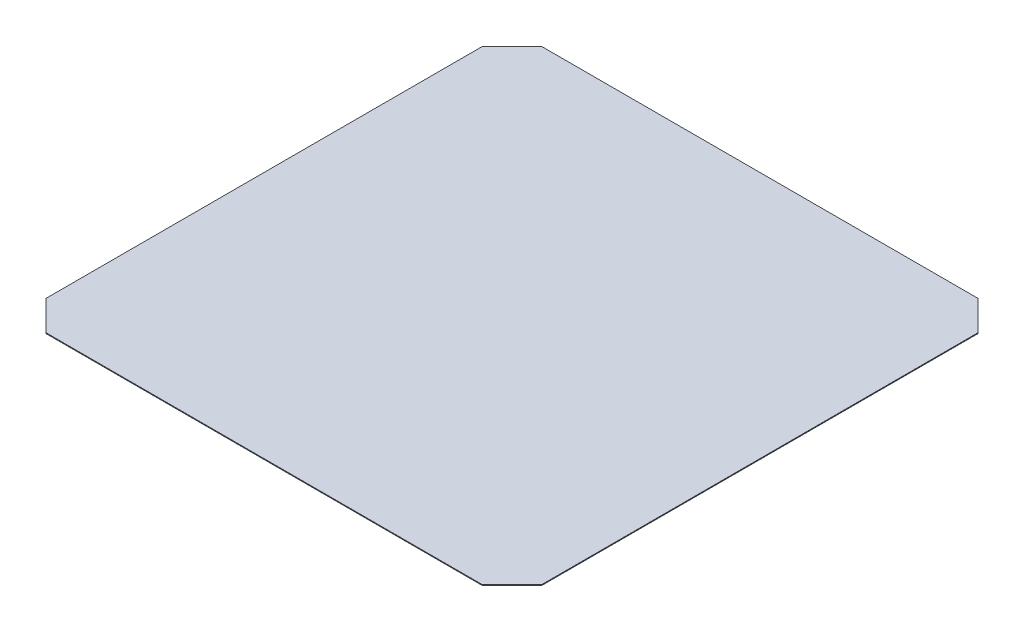
SolidWorks part; units mm, degrees
ref_plane "Alzado" through (0, 0, 0) normal (0, 0, 1) x (1, 0, 0)
ref_plane "Planta" through (0, 0, 0) normal (0, 1, 0) x (1, 0, 0)
ref_plane "Vista lateral" through (0, 0, 0) normal (1, 0, 0) x (0, 0, -1)
sketch "Croquis2" plane through (0, 0, 0) normal (0, 1, 0) x (1, 0, 0)
  line L0 (-62.5, 0) -> (62.5, 0) construction
  line L1 (0, -62.5) -> (0, 62.5) construction
  line L2 (-62.5, 0) -> (-62.5, 55)
  line L3 (-62.5, 55) -> (-55, 62.5)
  line L4 (-55, 62.5) -> (55, 62.5)
  line L5 (55, 62.5) -> (62.5, 55)
  line L6 (62.5, 55) -> (62.5, -55)
  line L7 (62.5, -55) -> (55, -62.5)
  line L8 (55, -62.5) -> (-55, -62.5)
  line L9 (-55, -62.5) -> (-62.5, -55)
  line L10 (-62.5, -55) -> (-62.5, 0)
  line L11 (-62.5, 55) -> (62.5, 55) construction
  line L12 (-55, 62.5) -> (-55, -62.5) construction
  point P6 (0, 0)
  point P8 (0, 0)
  point P14 (-8.9969, 42.1842)
  point P16 (-17.7362, 32.9849)
  dimension "D1" = 110
  dimension "D2" = 125
extrude "Saliente-Extruir1" add sketch "Croquis2" along normal blind 0.2
